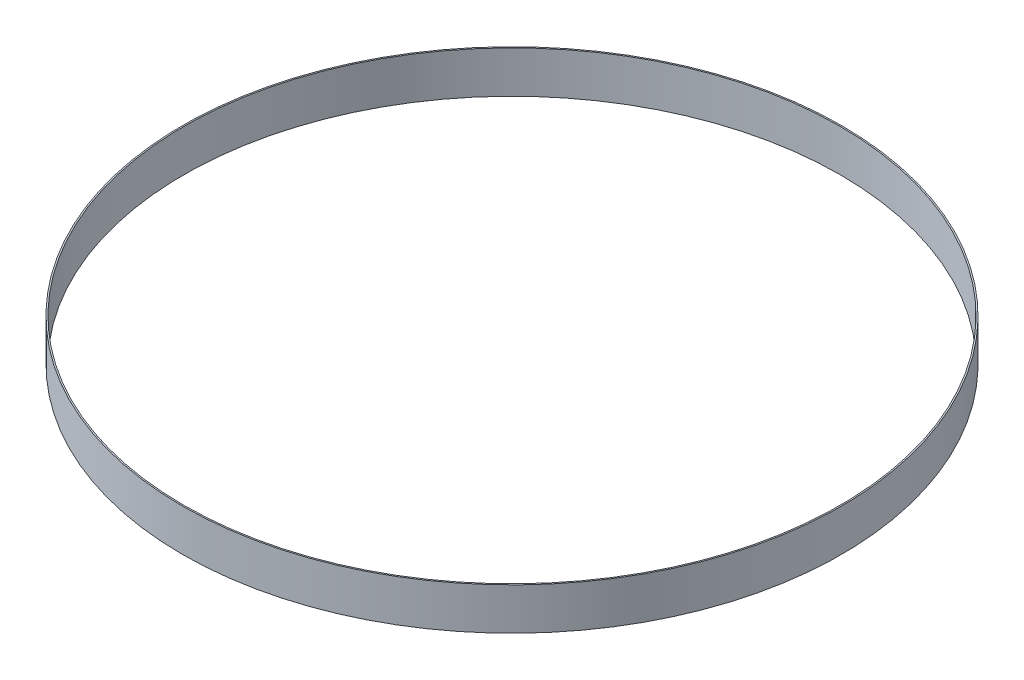
SolidWorks part; units mm, degrees
material "AISI 316 Stainless Steel Sheet (SS)"
ref_plane "Front Plane" through (0, 0, 0) normal (0, 0, 1) x (1, 0, 0)
ref_plane "Top Plane" through (0, 0, 0) normal (0, 1, 0) x (1, 0, 0)
ref_plane "Right Plane" through (0, 0, 0) normal (1, 0, 0) x (0, 0, -1)
sketch "Sketch1" plane through (0, 0, 0) normal (0, 1, 0) x (1, 0, 0)
  circle A0 centre (0, 0) radius 235
  circle A1 centre (0, 0) radius 236
  dimension "D1" = 470
  dimension "D2" = 472
  dimension "D3" = 1
extrude "Boss-Extrude1" add sketch "Sketch1" along normal mid plane 30
